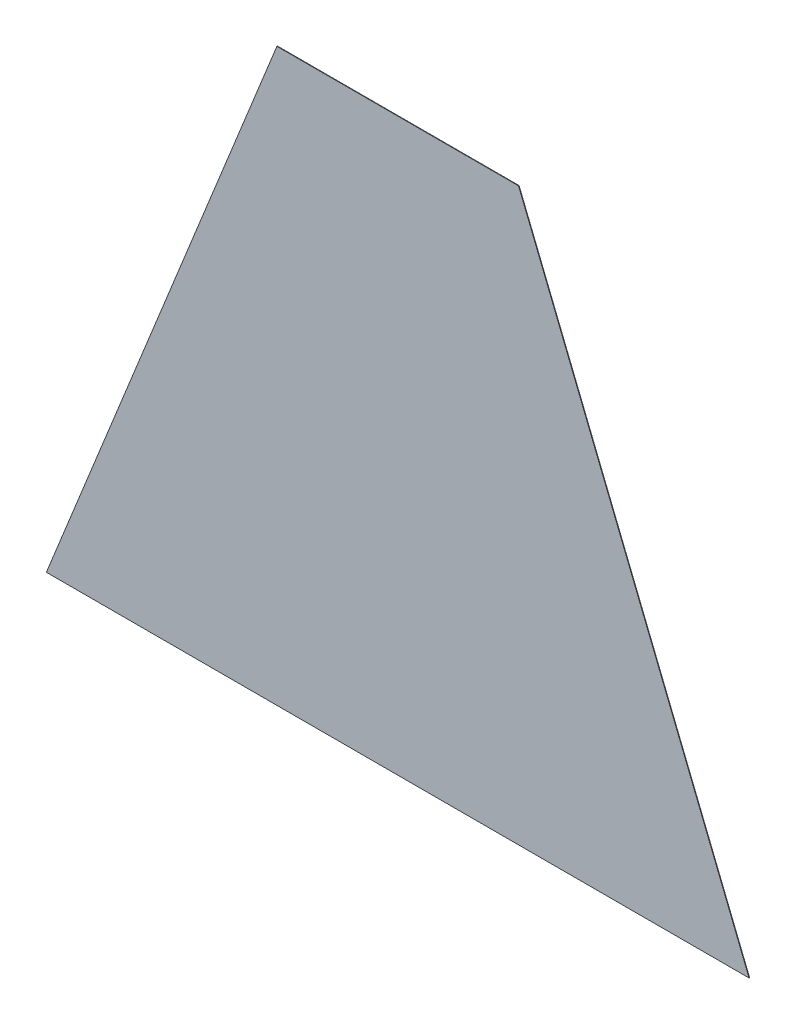
SolidWorks part; units mm, degrees
ref_plane "Front Plane" through (0, 0, 0) normal (0, 0, 1) x (1, 0, 0)
ref_plane "Top Plane" through (0, 0, 0) normal (0, 1, 0) x (1, 0, 0)
ref_plane "Right Plane" through (0, 0, 0) normal (1, 0, 0) x (0, 0, -1)
sketch "Sketch1" plane through (0, 0, 0) normal (0, 0, 1) x (1, 0, 0)
  line L9 (-15.6755, 3910.7286) -> (-1109.4146, 1202.765)
  line L15 (-1109.4146, 1202.765) -> (2224.5818, 1202.765)
  line L24 (-15.6755, 3910.7286) -> (1130.8427, 3910.7286)
  line L25 (2224.5818, 1202.765) -> (1130.8427, 3910.7286)
extrude "Boss-Extrude1" add sketch "Sketch1" along normal blind 2.54
